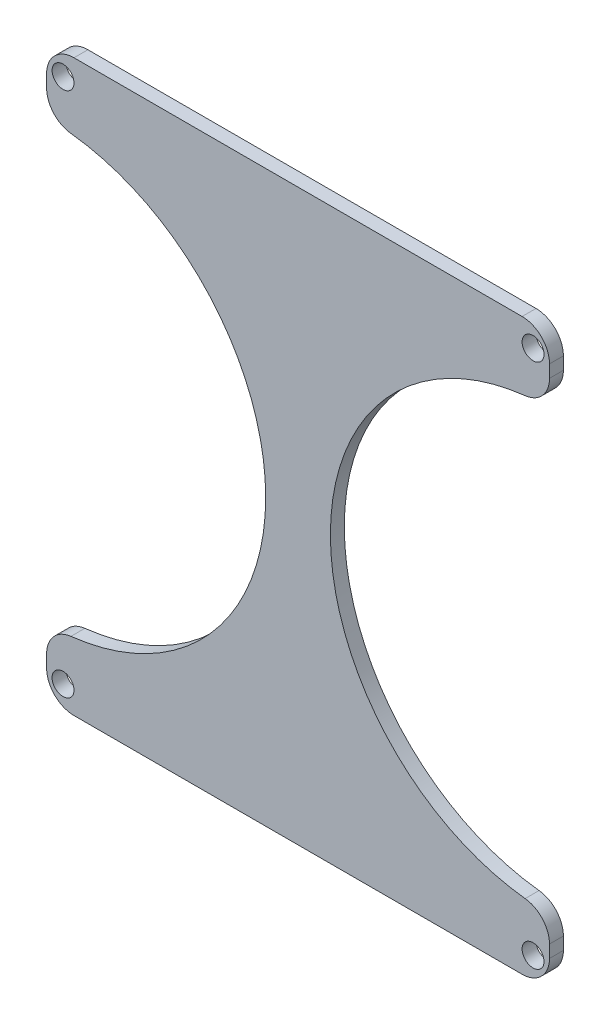
SolidWorks part; units mm, degrees
ref_plane "Front Plane" through (0, 0, 0) normal (0, 0, 1) x (1, 0, 0)
ref_plane "Top Plane" through (0, 0, 0) normal (0, 1, 0) x (1, 0, 0)
ref_plane "Right Plane" through (0, 0, 0) normal (1, 0, 0) x (0, 0, -1)
sketch "Sketch1" plane through (0, 0, 0) normal (0, 0, 1) x (1, 0, 0)
  line L1 (-429.7636, 215.3594) -> (-343.9543, 215.3594)
  line L2 (-429.7636, 215.3594) -> (-429.7636, 311.3594)
  line L3 (-429.7636, 311.3594) -> (-343.9543, 311.3594)
  line L4 (-343.9543, 215.3594) -> (-343.9543, 311.3594)
  circle A0 centre (-343.9543, 311.3594) radius 2
  circle A1 centre (-429.7636, 311.3594) radius 2
  circle A2 centre (-429.7636, 215.3594) radius 2
  circle A3 centre (-343.9543, 215.3594) radius 2
sketch "Sketch2" plane through (0, 0, 0) normal (0, 0, 1) x (1, 0, 0)
  line L1 (-432.7636, 211.3594) -> (-340.9543, 211.3594)
  line L2 (-432.7636, 211.3594) -> (-432.7636, 315.3594)
  line L3 (-432.7636, 315.3594) -> (-340.9543, 315.3594)
  line L4 (-340.9543, 211.3594) -> (-340.9543, 315.3594)
extrude "Boss-Extrude1" add sketch "Sketch2" along normal blind 2.54 contours L3 L4 L1 L2
extrude "Cut-Extrude1" cut sketch "Sketch1" along normal through all contours A0 | A1 | A2 | A3
sketch "Sketch3" plane through (0, 0, 0) normal (0, 0, -1) x (-1, 0, 0)
  line L0 (386.8589, 315.3594) -> (386.8589, 211.3594)
  line L1 (432.7636, 315.3594) -> (340.9543, 315.3594) construction
  line L2 (432.7636, 211.3594) -> (340.9543, 211.3594) construction
  line L4 (340.9543, 211.3594) -> (340.9543, 315.3594) construction
  line L5 (340.9543, 263.3594) -> (432.7636, 263.3594)
  line L6 (432.7636, 211.3594) -> (432.7636, 315.3594) construction
  arc A0 (380.9543, 263.3594) -> (340.9543, 223.3594) centre (340.9543, 263.3594) cw
  circle A1 centre (340.9543, 263.3594) radius 40
  circle A4 centre (432.7636, 263.3594) radius 40
  line M5 (432.7636, 211.3594) -> (432.7636, 315.3594)
  line M7 (340.9543, 315.3594) -> (340.9543, 211.3594)
extrude "Cut-Extrude2" cut sketch "Sketch3" against normal blind 10 contours A0 L5 M7 | L5 A1 M7 | L5 A4 M5 | A4 L5 M5
fillet "Fillet1" radius 5 8 edges at (-432.7636, 211.3594, 1.27) (-432.7636, 303.3594, 1.27) (-432.7636, 223.3594, 1.27) (-432.7636, 315.3594, 1.27) (-340.9543, 315.3594, 1.27) (-340.9543, 223.3594, 1.27) (-340.9543, 303.3594, 1.27) (-340.9543, 211.3594, 1.27)
